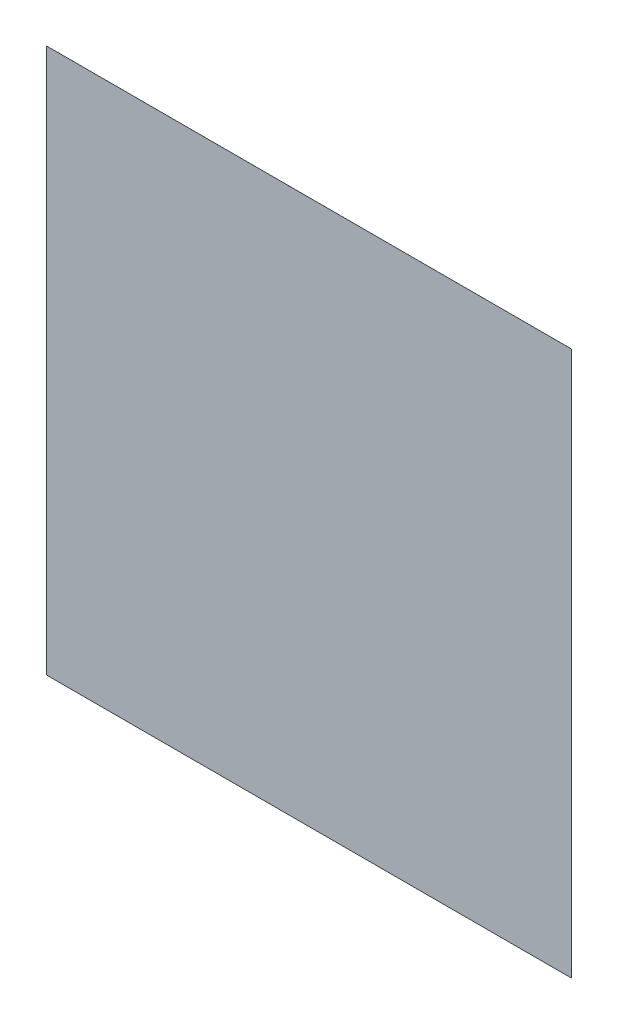
SolidWorks part; units mm, degrees
ref_plane "Front Plane" through (0, 0, 0) normal (0, 0, 1) x (1, 0, 0)
ref_plane "Top Plane" through (0, 0, 0) normal (0, 1, 0) x (1, 0, 0)
ref_plane "Right Plane" through (0, 0, 0) normal (1, 0, 0) x (0, 0, -1)
sketch "Sketch1" plane through (0, 0, 0) normal (0, 0, 1) x (1, 0, 0)
  line L0 (-5.1508, -4.9168) -> (4.9162, -4.9168)
  line L1 (4.9162, -4.9168) -> (4.9162, 5.5386)
  line L2 (4.9162, 5.5386) -> (-5.1508, 5.5386)
  line L3 (-5.1508, 5.5386) -> (-5.1508, -4.9168)
extrude "Boss-Extrude1" add sketch "Sketch1" along normal blind 0.0003 from offset 0
